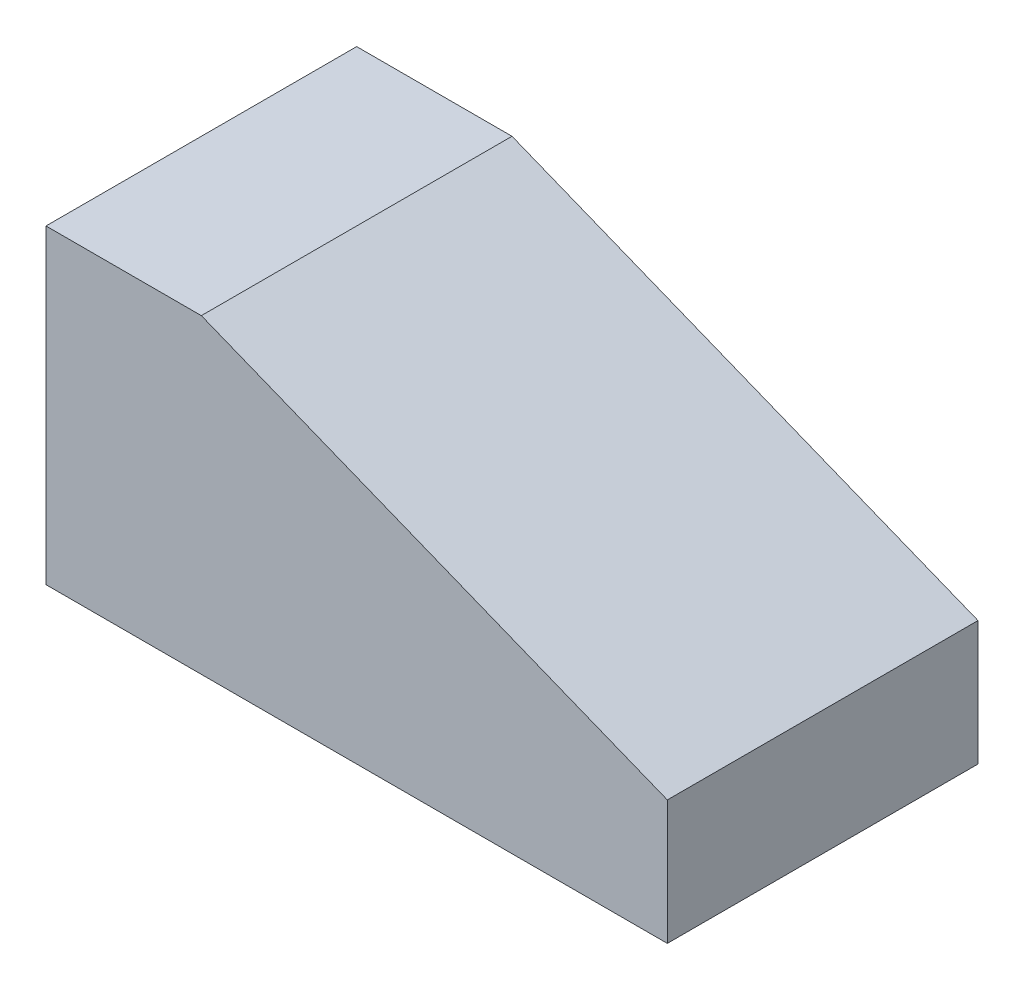
SolidWorks part; units mm, degrees
ref_plane "Front Plane" through (0, 0, 0) normal (0, 0, 1) x (1, 0, 0)
ref_plane "Top Plane" through (0, 0, 0) normal (0, 1, 0) x (1, 0, 0)
ref_plane "Right Plane" through (0, 0, 0) normal (1, 0, 0) x (0, 0, -1)
sketch "Sketch1" plane through (0, 0, 0) normal (0, 0, 1) x (1, 0, 0)
  line L0 (0, 0) -> (0, 50)
  line L1 (0, 50) -> (25, 50)
  line L2 (25, 50) -> (100, 20)
  line L3 (100, 20) -> (100, 0)
  line L4 (100, 0) -> (0, 0)
  dimension "D1" = 50
  dimension "D2" = 100
  dimension "D3" = 25
  dimension "D4" = 20
extrude "Boss-Extrude1" add sketch "Sketch1" along normal blind 50
